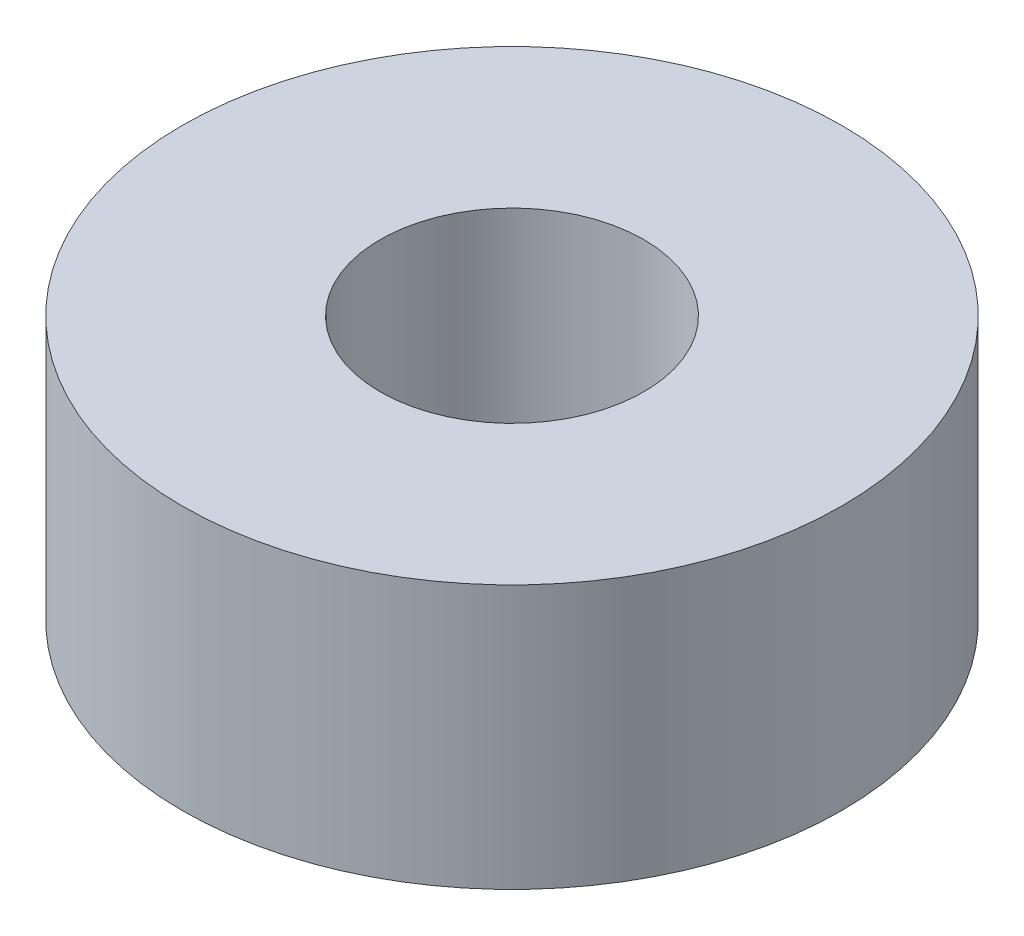
SolidWorks part; units mm, degrees
material "AISI 304"
ref_plane "前视基准面" through (0, 0, 0) normal (0, 0, 1) x (1, 0, 0)
ref_plane "上视基准面" through (0, 0, 0) normal (0, 1, 0) x (1, 0, 0)
ref_plane "右视基准面" through (0, 0, 0) normal (1, 0, 0) x (0, 0, -1)
sketch "草图1" plane through (0, 0, 0) normal (0, 1, 0) x (1, 0, 0)
  circle A0 centre (0, 0) radius 2.5
  circle A1 centre (0, 0) radius 1
  dimension "D1" = 2
  dimension "D2" = 5
extrude "凸台-拉伸1" add sketch "草图1" along normal blind 2
